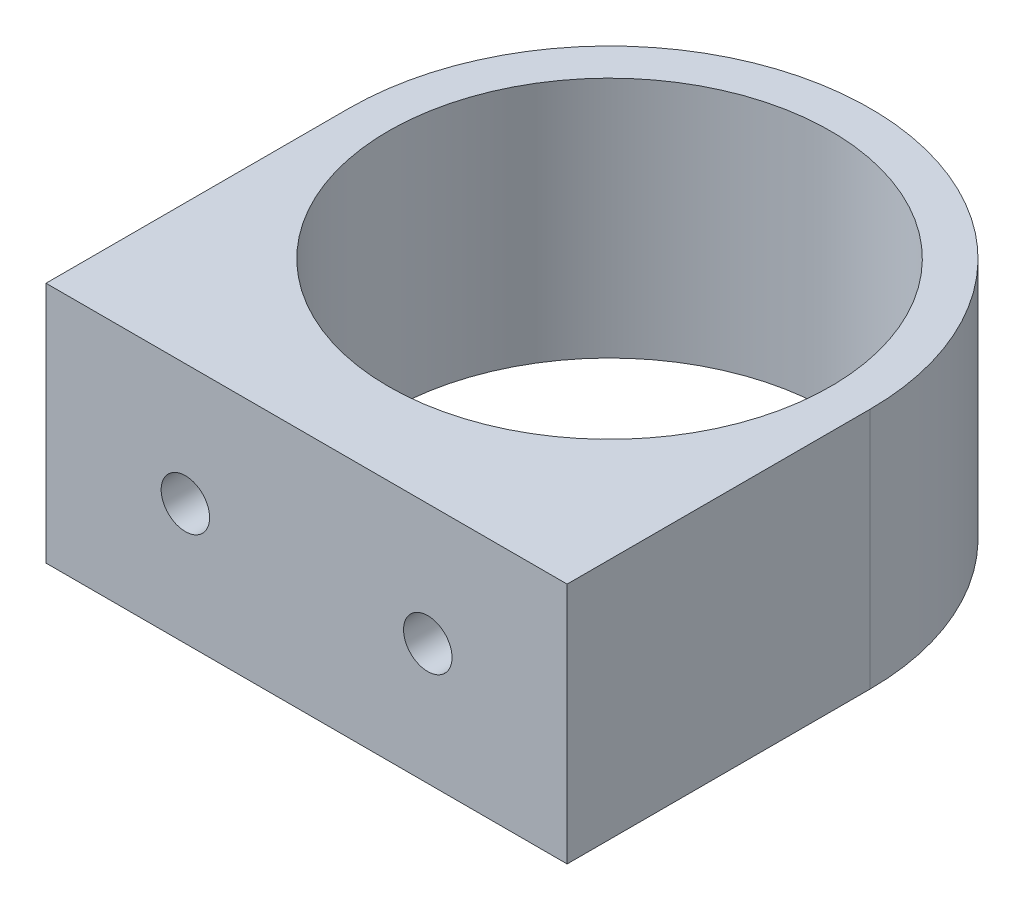
SolidWorks part; units mm, degrees
ref_plane "Front Plane" through (0, 0, 0) normal (0, 0, 1) x (1, 0, 0)
ref_plane "Top Plane" through (0, 0, 0) normal (0, 1, 0) x (1, 0, 0)
ref_plane "Right Plane" through (0, 0, 0) normal (1, 0, 0) x (0, 0, -1)
sketch "Sketch1" plane through (0, 0, 0) normal (0, 1, 0) x (1, 0, 0)
  line L0 (-21.5, 0) -> (-21.5, -25)
  line L1 (-21.5, -25) -> (21.5, -25)
  line L2 (21.5, -25) -> (21.5, 0)
  circle A0 centre (0, 0) radius 21.5
  circle A1 centre (0, 0) radius 18.25
  dimension "D1" = 43
  dimension "D3" = 36.5
  dimension "D2" = 25
extrude "Boss-Extrude1" add sketch "Sketch1" along normal blind 20 contours A0 L0 L1 L2 | A0 A1
sketch "Sketch2" plane through (0, 0, 25) normal (0, 0, 1) x (1, 0, 0)
  line L0 (-21.5, 20) -> (21.5, 20) construction
  circle A0 centre (-10, 10) radius 2
  circle A1 centre (10, 10) radius 2
  dimension "D1" = 4
  dimension "D2" = 4
  dimension "D3" = 20
  dimension "D4" = 10
  dimension "D5" = 10
  dimension "D6" = 10
extrude "Cut-Extrude1" cut sketch "Sketch2" against normal blind 10
